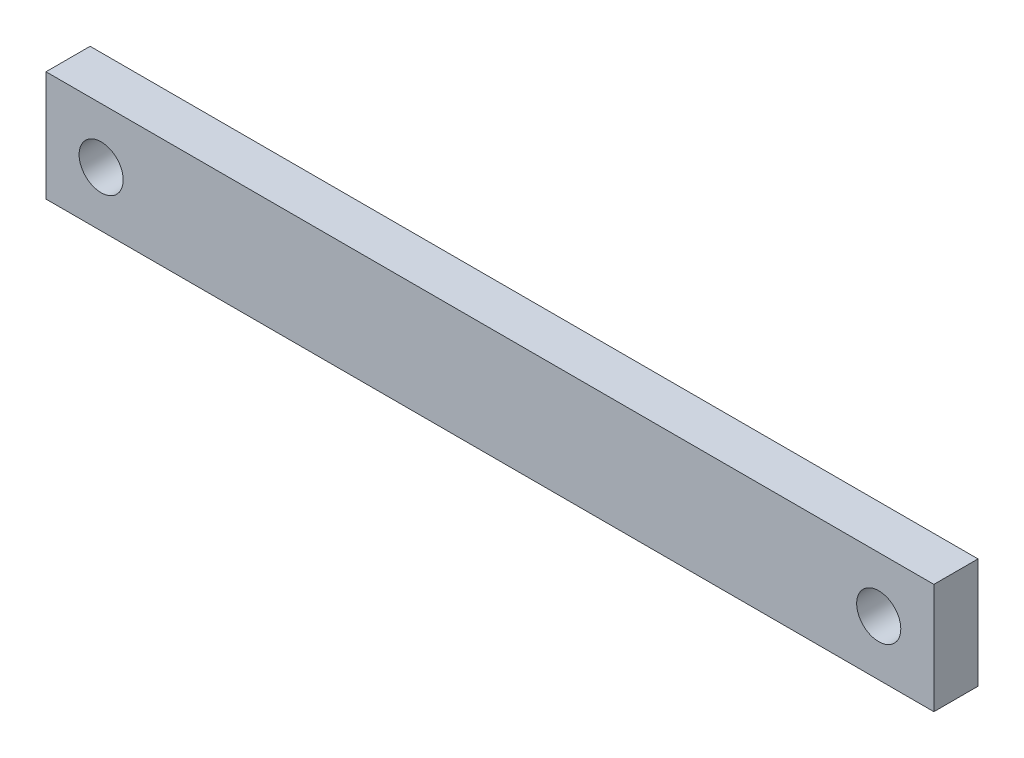
SolidWorks part; units mm, degrees
ref_plane "Front Plane" through (0, 0, 0) normal (0, 0, 1) x (1, 0, 0)
ref_plane "Top Plane" through (0, 0, 0) normal (0, 1, 0) x (1, 0, 0)
ref_plane "Right Plane" through (0, 0, 0) normal (1, 0, 0) x (0, 0, -1)
sketch "Sketch1" plane through (0, 0, 0) normal (0, 0, 1) x (1, 0, 0)
  line L0 (-80.5, 0) -> (80.5, 0) construction
  line L1 (80.5, 10) -> (-80.5, 10)
  line L2 (80.5, 10) -> (80.5, -10)
  line L3 (80.5, -10) -> (-80.5, -10)
  line L4 (-80.5, 10) -> (-80.5, -10)
  line L5 (80.5, 10) -> (-80.5, -10) construction
  line L6 (80.5, -10) -> (-80.5, 10) construction
  circle A0 centre (-70.5, 0) radius 4
  circle A1 centre (70.5, 0) radius 4
  point P0 (0, 0)
  point P8 (-70.5, 0)
  point P9 (70.5, 0)
  dimension "D5" = 8
  dimension "D1" = 161
  dimension "D2" = 20
  dimension "D3" = 141
  dimension "D4" = 10
extrude "Boss-Extrude1" add sketch "Sketch1" along normal blind 8
